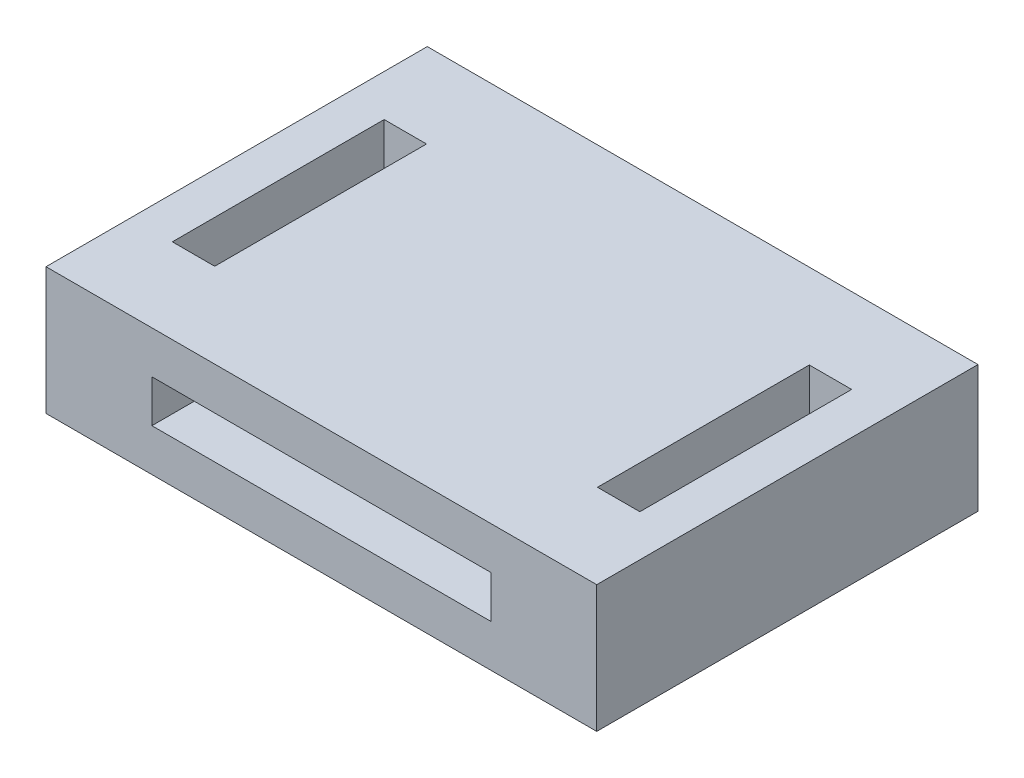
SolidWorks part; units mm, degrees
ref_plane "Front Plane" through (0, 0, 0) normal (0, 0, 1) x (1, 0, 0)
ref_plane "Top Plane" through (0, 0, 0) normal (0, 1, 0) x (1, 0, 0)
ref_plane "Right Plane" through (0, 0, 0) normal (1, 0, 0) x (0, 0, -1)
sketch "Sketch1" plane through (0, 0, 0) normal (0, 1, 0) x (1, 0, 0)
  line L0 (-16.51, 0) -> (-12.7449, 0) construction
  line L1 (-16.51, -11.43) -> (16.51, -11.43)
  line L2 (-16.51, -11.43) -> (-16.51, 11.43)
  line L3 (-16.51, 11.43) -> (16.51, 11.43)
  line L4 (16.51, -11.43) -> (16.51, 11.43)
  line L5 (-16.51, -11.43) -> (16.51, 11.43) construction
  line L6 (-16.51, 11.43) -> (16.51, -11.43) construction
  line L7 (0, -1000) -> (0, 49000) construction
  line L8 (-11.4749, -6.35) -> (-14.0149, -6.35)
  line L9 (-11.4749, -6.35) -> (-11.4749, 6.35)
  line L10 (-11.4749, 6.35) -> (-14.0149, 6.35)
  line L11 (-14.0149, -6.35) -> (-14.0149, 6.35)
  line L12 (-11.4749, -6.35) -> (-14.0149, 6.35) construction
  line L13 (-11.4749, 6.35) -> (-14.0149, -6.35) construction
  line L14 (11.4749, 6.35) -> (14.0149, 6.35)
  line L15 (14.0149, -6.35) -> (14.0149, 6.35)
  line L16 (11.4749, -6.35) -> (14.0149, -6.35)
  line L17 (11.4749, -6.35) -> (11.4749, 6.35)
  point P0 (0, 0)
  dimension "D1" = 22.86
  dimension "D2" = 33.02
  dimension "D3" = 12.7
  dimension "D4" = 2.54
  dimension "D5" = 2.4951
extrude "Boss-Extrude2" add sketch "Sketch1" along normal blind 2.54
sketch "Sketch3" plane through (0, 2.54, 0) normal (0, 1, 0) x (1, 0, 0)
  line L0 (0, 11.43) -> (0, 1.27) construction
  line L1 (16.51, 11.43) -> (-16.51, 11.43) construction
  line L2 (5.3189, 1.27) -> (-5.3189, 1.27) construction
  circle A0 centre (-5.3189, 1.27) radius 1.016
  circle A1 centre (5.3189, 1.27) radius 1.016
extrude "Boss-Extrude3" add sketch "Sketch3" along normal blind 2.54
ref_plane "Plane2" through (0, 5.08, 0) normal (0, 1, 0) x (1, 0, 0)
sketch "Sketch4" plane through (0, 5.08, 0) normal (0, 1, 0) x (1, 0, 0)
  line L0 (11.4749, 6.35) -> (11.4749, -6.35) construction
  line L1 (-16.51, 11.43) -> (16.51, 11.43)
  line L2 (-16.51, 11.43) -> (-16.51, -11.43)
  line L3 (-16.51, -11.43) -> (16.51, -11.43)
  line L4 (16.51, 11.43) -> (16.51, -11.43)
  line L5 (-14.0149, 6.35) -> (-11.4749, 6.35)
  line L6 (-14.0149, 6.35) -> (-14.0149, -6.35)
  line L7 (-14.0149, -6.35) -> (-11.4749, -6.35)
  line L8 (-11.4749, 6.35) -> (-11.4749, -6.35)
  line L9 (11.4749, 6.35) -> (14.0149, 6.35)
  line L10 (11.4749, 6.35) -> (11.4749, -6.35)
  line L11 (11.4749, -6.35) -> (14.0149, -6.35)
  line L12 (14.0149, 6.35) -> (14.0149, -6.35)
sketch "Sketch5" plane through (0, 2.54, 0) normal (0, 1, 0) x (1, 0, 0)
  line L0 (-16.51, -11.43) -> (-16.51, 11.43)
  line L1 (16.51, 11.43) -> (-16.51, 11.43) construction
  line L2 (-16.51, 11.43) -> (-16.51, -11.43) construction
  line L5 (-16.51, -11.43) -> (16.51, -11.43) construction
  line L8 (-16.51, -11.43) -> (-10.16, -11.43)
  line L11 (-10.16, -11.43) -> (-10.16, 6.35)
  line L12 (-10.16, 6.35) -> (10.16, 6.35)
  line L13 (10.16, 6.35) -> (10.16, -11.43)
  line L14 (-16.51, -11.43) -> (16.51, -11.43) construction
  line L15 (10.16, -11.43) -> (16.51, -11.43)
  line L16 (16.51, -11.43) -> (16.51, 11.43)
  line L17 (16.51, 11.43) -> (-16.51, 11.43)
  line L21 (-14.0149, 6.35) -> (-11.4749, 6.35)
  line L22 (-14.0149, 6.35) -> (-14.0149, -6.35)
  line L23 (-14.0149, -6.35) -> (-11.4749, -6.35)
  line L24 (-11.4749, 6.35) -> (-11.4749, -6.35)
  line L25 (11.4749, 6.35) -> (14.0149, 6.35)
  line L26 (11.4749, 6.35) -> (11.4749, -6.35)
  line L27 (11.4749, -6.35) -> (14.0149, -6.35)
  line L28 (14.0149, 6.35) -> (14.0149, -6.35)
  dimension "D1" = 6.35
  dimension "D2" = 17.78
extrude "Boss-Extrude6" add sketch "Sketch4" along normal blind 2.54
extrude "Boss-Extrude7" add sketch "Sketch5" along normal up to surface (2.54 mm away) up to face at (-5.3189, 5.08, -0.254)
